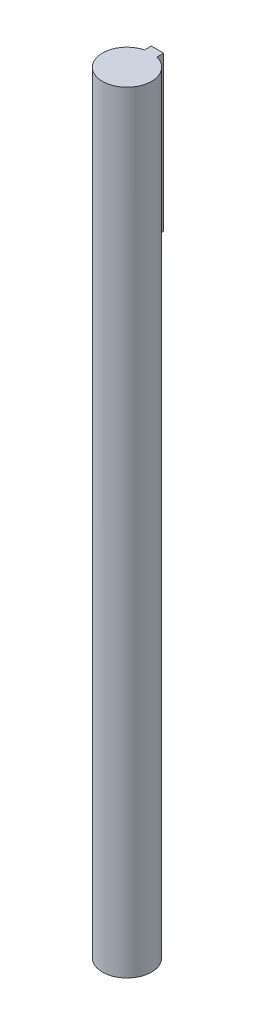
SolidWorks part; units mm, degrees
ref_plane "Front Plane" through (0, 0, 0) normal (0, 0, 1) x (1, 0, 0)
ref_plane "Top Plane" through (0, 0, 0) normal (0, 1, 0) x (1, 0, 0)
ref_plane "Right Plane" through (0, 0, 0) normal (1, 0, 0) x (0, 0, -1)
sketch "Sketch1" plane through (0, 0, 0) normal (0, 1, 0) x (1, 0, 0)
  circle A0 centre (0, 0) radius 9.54
  point P1 (0, 0)
  dimension "D1" = 9.54
extrude "Boss-Extrude1" add sketch "Sketch1" along normal blind 300
sketch "Sketch2" plane through (0, 300, 0) normal (0, 1, 0) x (1, 0, 0)
  line L2 (-2.4, 9.2332) -> (-2.4, 11.87)
  line L3 (-2.4, 11.87) -> (2.4, 11.87)
  line L4 (2.4, 9.2332) -> (2.4, 11.87)
  circle A0 centre (0, 0) radius 9.54 construction
  arc A2 (2.4, 9.2332) -> (-2.4, 9.2332) centre (0, 0) ccw
  point P0 (0, 9.54)
  dimension "D1" = 4.8
  dimension "D2" = 11.87
extrude "Boss-Extrude2" add sketch "Sketch2" against normal blind 60
